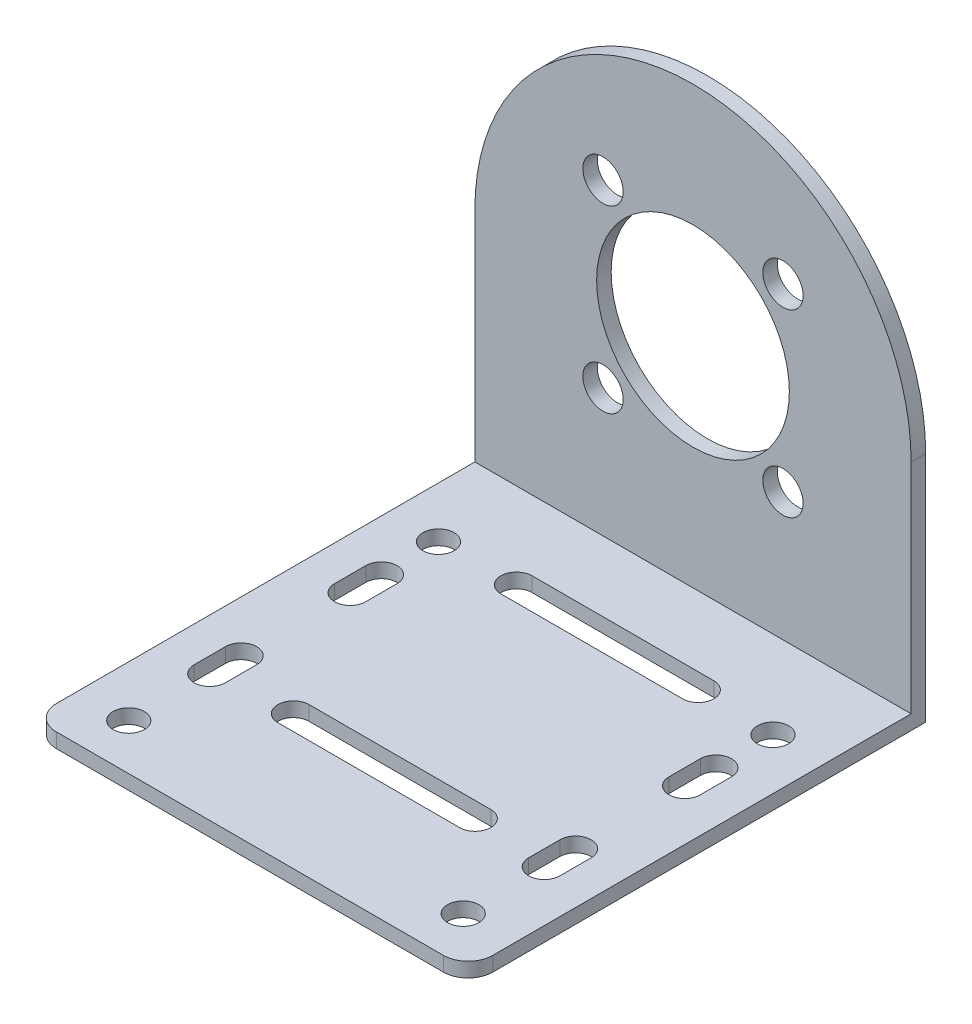
SolidWorks part; units mm, degrees
ref_plane "Front Plane" through (0, 0, 0) normal (0, 0, 1) x (1, 0, 0)
ref_plane "Top Plane" through (0, 0, 0) normal (0, 1, 0) x (1, 0, 0)
ref_plane "Right Plane" through (0, 0, 0) normal (1, 0, 0) x (0, 0, -1)
sketch "Sketch1" plane through (0, 0, 0) normal (0, 1, 0) x (1, 0, 0)
  line L0 (-12.5, -12.985) -> (12.5, -12.985) construction
  line L2 (-26.6046, -31.465) -> (26.6046, -31.465)
  line L3 (-30, -28.0696) -> (-30, 31.465)
  line L4 (-30, 31.465) -> (30, 31.465)
  line L5 (30, -28.0696) -> (30, 31.465)
  line L6 (-30, -31.465) -> (30, 31.465) construction
  line L7 (-30, 31.465) -> (30, -31.465) construction
  line L9 (-12.5, 17.6882) -> (12.5, 17.6882) construction
  line L10 (-12.5, 19.8382) -> (12.5, 19.8382)
  line L11 (-12.5, 15.5382) -> (12.5, 15.5382)
  line L12 (-23, 9.615) -> (-23, 5.315) construction
  line L13 (-20.85, 9.615) -> (-20.85, 5.315)
  line L14 (-25.15, 9.615) -> (-25.15, 5.315)
  line L15 (-23, -9.685) -> (-23, -13.985) construction
  line L16 (-20.85, -9.685) -> (-20.85, -13.985)
  line L17 (-25.15, -9.685) -> (-25.15, -13.985)
  line L18 (-12.5, -10.835) -> (12.5, -10.835)
  line L19 (-12.5, -15.135) -> (12.5, -15.135)
  line L20 (0, 11.5674) -> (0, -3.1271) construction
  line L21 (23, -9.685) -> (23, -13.985) construction
  line L22 (20.85, -9.685) -> (20.85, -13.985)
  line L23 (25.15, -9.685) -> (25.15, -13.985)
  line L24 (23, 9.615) -> (23, 5.315) construction
  line L25 (20.85, 9.615) -> (20.85, 5.315)
  line L26 (25.15, 9.615) -> (25.15, 5.315)
  arc A2 (-12.5, 19.8382) -> (-12.5, 15.5382) centre (-12.5, 17.6882) ccw
  arc A3 (12.5, 15.5382) -> (12.5, 19.8382) centre (12.5, 17.6882) ccw
  arc A4 (-20.85, 9.615) -> (-25.15, 9.615) centre (-23, 9.615) ccw
  arc A5 (-25.15, 5.315) -> (-20.85, 5.315) centre (-23, 5.315) ccw
  arc A6 (-20.85, -9.685) -> (-25.15, -9.685) centre (-23, -9.685) ccw
  arc A7 (-25.15, -13.985) -> (-20.85, -13.985) centre (-23, -13.985) ccw
  circle A8 centre (-23, -25.135) radius 2.15
  arc A9 (26.6046, -31.465) -> (30, -28.0696) centre (26.6046, -28.0696) ccw
  arc A10 (-26.6046, -31.465) -> (-30, -28.0696) centre (-26.6046, -28.0696) cw
  circle A11 centre (-23, 17.465) radius 2.15
  arc A12 (-12.5, -10.835) -> (-12.5, -15.135) centre (-12.5, -12.985) ccw
  arc A13 (12.5, -15.135) -> (12.5, -10.835) centre (12.5, -12.985) ccw
  circle A14 centre (23, -25.135) radius 2.15
  arc A15 (20.85, -9.685) -> (25.15, -9.685) centre (23, -9.685) cw
  arc A16 (25.15, -13.985) -> (20.85, -13.985) centre (23, -13.985) cw
  arc A17 (20.85, 9.615) -> (25.15, 9.615) centre (23, 9.615) cw
  arc A18 (25.15, 5.315) -> (20.85, 5.315) centre (23, 5.315) cw
  circle A19 centre (23, 17.465) radius 2.15
  point P1 (0, 0)
  point P8 (0, -12.985)
  point P13 (0, 17.6882)
  point P22 (-23, 7.465)
  point P27 (-23, -11.835)
  point P48 (23, -11.835)
  point P57 (23, 7.465)
  dimension "D1" = 6.33
  dimension "D3" = 4.3
  dimension "D9" = 4.3
  dimension "D14" = 2.15
  dimension "D15" = 2.15
  dimension "D16" = 2.15
  dimension "D17" = 2.15
  dimension "D24" = 3.3954
  dimension "D2" = 7
  dimension "D4" = 11.15
  dimension "D5" = 15
  dimension "D6" = 4.3
  dimension "D7" = 4.3
  dimension "D8" = 7
  dimension "D10" = 7
  dimension "D11" = 25
  dimension "D12" = 18.48
  dimension "D13" = 25
  dimension "D18" = 30.6732
  dimension "D19" = 7.85
  dimension "D20" = 14
  dimension "D21" = 60
  dimension "D22" = 30
  dimension "D23" = 30
extrude "Boss-Extrude1" add sketch "Sketch1" along normal blind 2
sketch "Sketch5" plane through (0, 0, -31.465) normal (0, 0, -1) x (-1, 0, 0)
  line L0 (-30, 2) -> (-30, 32)
  line L1 (-30, 32) -> (30, 32) construction
  line L2 (30, 32) -> (30, 2)
  line L3 (0, 32) -> (12.3744, 44.3744) construction
  arc A0 (-30, 32) -> (30, 32) centre (0, 32) cw
  circle A1 centre (0, 32) radius 13.25
  circle A2 centre (0, 32) radius 17.5 construction
  circle A3 centre (12.3744, 44.3744) radius 2.7744
  circle A4 centre (-12.3744, 44.3744) radius 2.7744
  circle A5 centre (-12.3744, 19.6256) radius 2.7744
  circle A6 centre (12.3744, 19.6256) radius 2.7744
  point P20 (0, 32)
  line M4 (30, 2) -> (-30, 2)
  dimension "D1" = 26.5
  dimension "D2" = 35
  dimension "D5" = 5.5489
  dimension "D3" = 30
  dimension "D4" = 45
  dimension "D6" = 4
extrude "Boss-Extrude2" add sketch "Sketch5" against normal blind 2 contours A0 L0 L2 A6 A5 A4 A3 A1 M4
